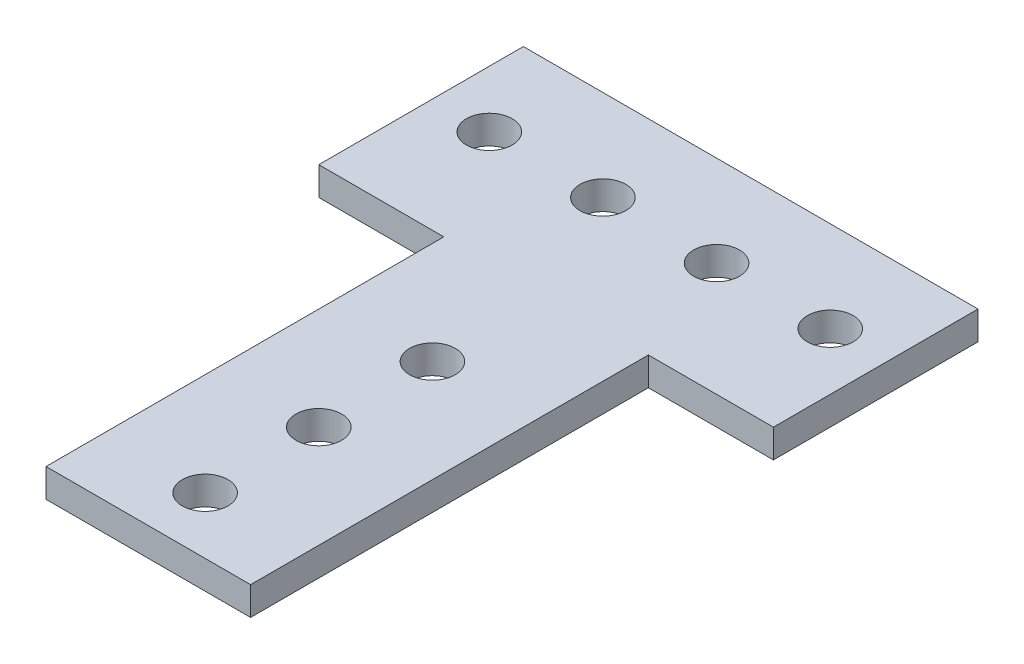
SolidWorks part; units mm, degrees
material "6061-T6 (SS)"
ref_plane "Front Plane" through (0, 0, 0) normal (0, 0, 1) x (1, 0, 0)
ref_plane "Top Plane" through (0, 0, 0) normal (0, 1, 0) x (1, 0, 0)
ref_plane "Right Plane" through (0, 0, 0) normal (1, 0, 0) x (0, 0, -1)
sketch "Sketch1" plane through (0, 0, 0) normal (0, 1, 0) x (1, 0, 0)
  line L0 (0, 0) -> (0, 44.45)
  line L1 (0, 44.45) -> (-13.97, 44.45)
  line L2 (-13.97, 44.45) -> (-13.97, 67.31)
  line L3 (-13.97, 67.31) -> (36.83, 67.31)
  line L4 (36.83, 67.31) -> (36.83, 44.45)
  line L5 (36.83, 44.45) -> (22.86, 44.45)
  line L6 (22.86, 44.45) -> (22.86, 0)
  line L7 (22.86, 0) -> (0, 0)
  dimension "D1" = 22.86
  dimension "D2" = 22.86
  dimension "D3" = 50.8
  dimension "D4" = 44.45
extrude "Boss-Extrude1" add sketch "Sketch1" along normal blind 3.175
sketch "Sketch2" plane through (0, 3.175, 0) normal (0, 1, 0) x (1, 0, 0)
  line L0 (-13.97, 67.31) -> (-13.97, 44.45) construction
  line L1 (-13.97, 44.45) -> (0, 44.45) construction
  line L2 (22.86, 44.45) -> (36.83, 44.45) construction
  circle A0 centre (-7.62, 57.15) radius 2.5527
  circle A1 centre (5.08, 57.15) radius 2.5527
  circle A2 centre (17.78, 57.15) radius 2.5527
  circle A3 centre (30.48, 57.15) radius 2.5527
  dimension "D1" = 5.1054
  dimension "D2" = 12.7
  dimension "D3" = 12.7
  dimension "D4" = 12.7
  dimension "D5" = 6.35
  dimension "D6" = 12.7
  dimension "D7" = 12.7
  dimension "D8" = 12.7
  dimension "D9" = 12.7
extrude "Cut-Extrude1" cut sketch "Sketch2" against normal through all
sketch "Sketch3" plane through (0, 3.175, 0) normal (0, 1, 0) x (1, 0, 0)
  line L0 (22.86, 0) -> (22.86, 44.45) construction
  line L1 (0, 0) -> (22.86, 0) construction
  circle A0 centre (11.43, 31.75) radius 2.5527
  circle A1 centre (11.43, 19.05) radius 2.5527
  circle A2 centre (11.43, 6.35) radius 2.5527
  dimension "D1" = 5.1054
  dimension "D2" = 11.43
  dimension "D3" = 12.7
  dimension "D4" = 12.7
  dimension "D5" = 19.05
  dimension "D6" = 11.43
  dimension "D7" = 11.43
extrude "Cut-Extrude2" cut sketch "Sketch3" against normal through all
